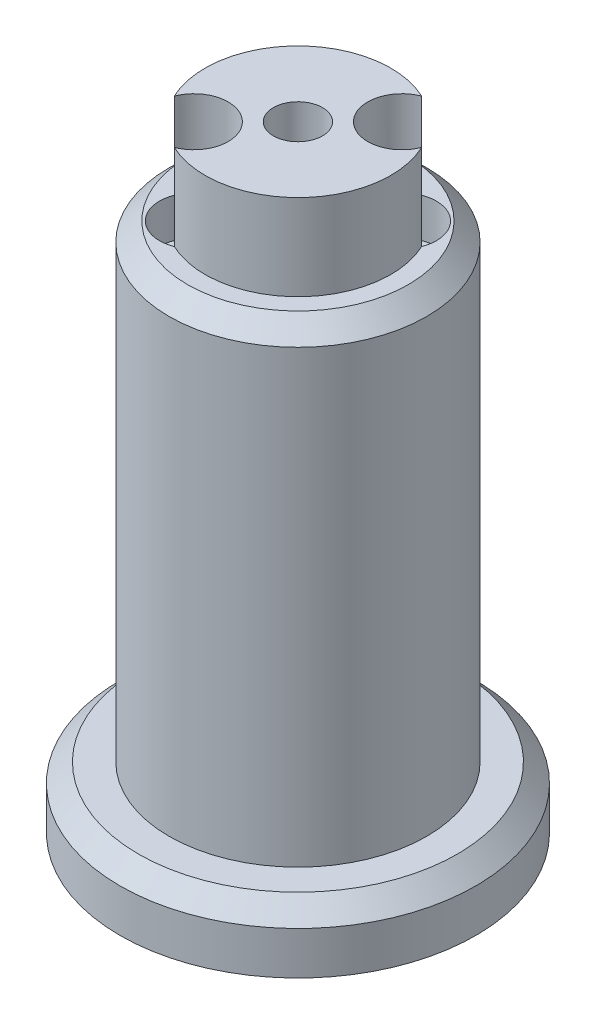
SolidWorks part; units mm, degrees
material "3DP Resin"
ref_plane "Front Plane" through (0, 0, 0) normal (0, 0, 1) x (1, 0, 0)
ref_plane "Top Plane" through (0, 0, 0) normal (0, 1, 0) x (1, 0, 0)
ref_plane "Right Plane" through (0, 0, 0) normal (1, 0, 0) x (0, 0, -1)
sketch "Sketch1" plane through (0, 0, 0) normal (0, 1, 0) x (1, 0, 0)
  circle A0 centre (0, 0) radius 14.5
  dimension "D1" = 29
extrude "Boss-Extrude1" add sketch "Sketch1" along normal blind 5
sketch "Sketch2" plane through (0, 0, 0) normal (0, -1, 0) x (1, 0, 0)
  circle A0 centre (0, 0) radius 13
  dimension "D1" = 26
extrude "Cut-Extrude1" cut sketch "Sketch2" against normal blind 3
sketch "Sketch6" plane through (0, 5, 0) normal (0, 1, 0) x (1, 0, 0)
  circle A0 centre (0, 0) radius 10.5
  dimension "D1" = 21
extrude "Boss-Extrude3" add sketch "Sketch6" along normal blind 45.2
sketch "Sketch3" plane through (0, 5, 0) normal (0, 1, 0) x (1, 0, 0)
  line L0 (14.5, 0) -> (-14.5, 0) construction
  line L1 (0, -14.5) -> (0, 14.5) construction
  line L2 (-4.2426, 4.2426) -> (0, 0) construction
  circle A0 centre (0, 0) radius 3
  circle A1 centre (0, 0) radius 14.5 construction
  circle A2 centre (0, 0) radius 6 construction
  circle A3 centre (-4.2426, 4.2426) radius 1.5
  circle A5 centre (4.2426, 4.2426) radius 1.5
  circle A6 centre (4.2426, -4.2426) radius 1.5
  circle A7 centre (-4.2426, -4.2426) radius 1.5
  point P7 (0, 0)
  point P11 (0, 0)
  point P23 (0, 0)
  dimension "D1" = 6
  dimension "D2" = 12
  dimension "D3" = 3
  dimension "D4" = 45
  dimension "D5" = 4
extrude "Cut-Extrude2" cut sketch "Sketch3" along normal blind 5 from surface at -2 starting at face at (0, 3, -13)
sketch "Sketch7" plane through (0, 50.2, 0) normal (0, 1, 0) x (1, 0, 0)
  circle A0 centre (0, 0) radius 10.5
  circle A1 centre (0, 0) radius 7.575
  dimension "D1" = 15.15
  dimension "D2" = 21
extrude "Bearing Support" cut sketch "Sketch7" against normal blind 7
sketch "Sketch8" plane through (0, 3, 0) normal (0, -1, 0) x (1, 0, 0)
  line L0 (-13, 0) -> (13, 0) construction
  line L1 (0, -13) -> (0, 13) construction
  line L2 (-4.2426, 4.2426) -> (0, 0) construction
  line L3 (0, 0) -> (4.2426, -4.2426) construction
  circle A0 centre (0, 0) radius 2
  circle A1 centre (0, 0) radius 13 construction
  circle A2 centre (0, 0) radius 13 construction
  circle A3 centre (-4.2426, 4.2426) radius 1.5
  circle A4 centre (0, 0) radius 6 construction
  circle A5 centre (4.2426, -4.2426) radius 1.5
  circle A6 centre (-4.2426, 4.2426) radius 1.5 construction
  point P6 (0, 0)
  point P31 (0, 0)
  dimension "D1" = 4
  dimension "D2" = 3
  dimension "D3" = 12
  dimension "D4" = 45
extrude "M4 Hole Bore" cut sketch "Sketch8" against normal through all
sketch "Sketch9" plane through (0, 50.2, 0) normal (0, 1, 0) x (1, 0, 0)
  circle A0 centre (4.2426, 4.2426) radius 1.5 construction
  circle A1 centre (-4.2426, -4.2426) radius 1.5 construction
  circle A2 centre (4.2426, 4.2426) radius 1.5 construction
  circle A3 centre (-4.2426, -4.2426) radius 1.5 construction
  circle A4 centre (4.2426, 4.2426) radius 2.8
  circle A5 centre (-4.2426, -4.2426) radius 2.8
  dimension "D1" = 5.6
extrude "M3 Bolt Recesses" cut sketch "Sketch9" against normal blind 10.2
chamfer "Chamfer1" distance 1.5 angle 45 2 edges at (0, 43.2, 10.5) (0, 5, 14.5)
